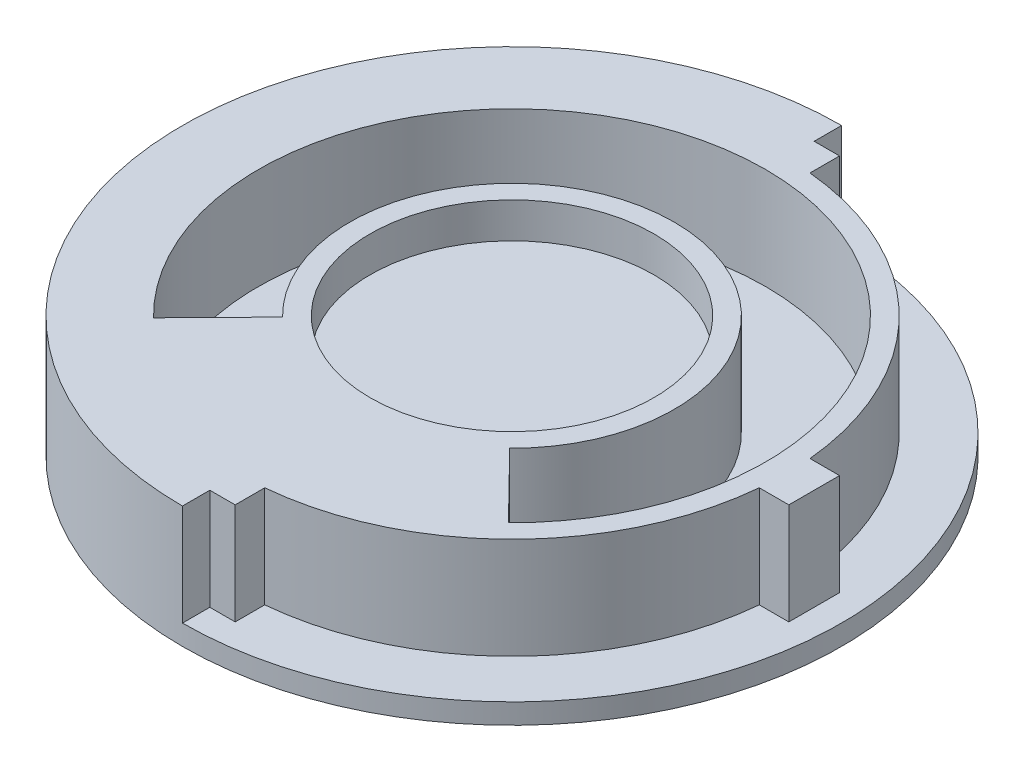
SolidWorks part; units mm, degrees
ref_plane "Front Plane" through (0, 0, 0) normal (0, 0, 1) x (1, 0, 0)
ref_plane "Top Plane" through (0, 0, 0) normal (0, 1, 0) x (1, 0, 0)
ref_plane "Right Plane" through (0, 0, 0) normal (1, 0, 0) x (0, 0, -1)
sketch "Sketch1" plane through (0, 0, 0) normal (0, 1, 0) x (1, 0, 0)
  line L0 (-17.5, -17.8536) -> (-11.2, -11.4263)
  line L1 (0, -55) -> (0, 55) construction
  line L2 (17.5, -17.8536) -> (11.2, -11.4263)
  line L4 (-17.5, -17.8536) -> (3.8221, -38.7535) construction
  circle A0 centre (0, 0) radius 27
  arc A1 (11.2, -11.4263) -> (-11.2, -11.4263) centre (0, 0) ccw
  arc A2 (17.5, -17.8536) -> (-17.5, -17.8536) centre (0, 0) ccw
  circle A3 centre (0, 0) radius 14
  arc A4 (16.5039, 11.7639) -> (14.35, -14.6399) centre (0.1913, -0.1952) cw construction
  circle A5 centre (0, 0) radius 19.9533 construction
  dimension "D1" = 54
  dimension "D2" = 2
  dimension "D3" = 9
  dimension "D4" = 2
  dimension "D5" = 35
extrude "Boss-Extrude1" add sketch "Sketch1" along normal blind 10
sketch "Sketch2" plane through (0, 0, 0) normal (0, -1, 0) x (1, 0, 0)
  circle A0 centre (0, 0) radius 32.5
  circle A1 centre (0, 0) radius 14 construction
  circle A2 centre (0, 0) radius 14 construction
  dimension "D1" = 65
extrude "Boss-Extrude2" add sketch "Sketch2" along normal blind 2
sketch "Sketch3" plane through (0, 0, 0) normal (0, 1, 0) x (1, 0, 0)
  line L0 (0, -5.5) -> (0, 5.5) construction
  line L1 (-2.5, 29.8) -> (2.5, 29.8)
  line L2 (-2.5, 29.8) -> (-2.5, 25.4032)
  line L3 (-2.5, 25.4032) -> (2.5, 25.4032)
  line L4 (2.5, 29.8) -> (2.5, 25.4032)
  line L5 (-2.5, 29.8) -> (2.5, 25.4032) construction
  line L6 (-2.5, 25.4032) -> (2.5, 29.8) construction
  line L7 (29.8, 2.5) -> (25.4032, 2.5)
  line L8 (29.8, 2.5) -> (29.8, -2.5)
  line L9 (29.8, -2.5) -> (25.4032, -2.5)
  line L10 (25.4032, 2.5) -> (25.4032, -2.5)
  line L11 (2.5, -29.8) -> (2.5, -25.4032)
  line L12 (2.5, -29.8) -> (-2.5, -29.8)
  line L13 (-2.5, -29.8) -> (-2.5, -25.4032)
  line L14 (2.5, -25.4032) -> (-2.5, -25.4032)
  line L15 (-29.8, -2.5) -> (-25.4032, -2.5)
  line L16 (-29.8, -2.5) -> (-29.8, 2.5)
  line L17 (-29.8, 2.5) -> (-25.4032, 2.5)
  line L18 (-25.4032, -2.5) -> (-25.4032, 2.5)
  circle A1 centre (0, 0) radius 27 construction
  point P0 (0, 27.6016)
  dimension "D2" = 29.8
  dimension "D1" = 5
  dimension "D3" = 4
extrude "Boss-Extrude3" add sketch "Sketch3" along normal blind 10
sketch "Sketch4" plane through (0, -2, 0) normal (0, -1, 0) x (1, 0, 0)
  circle A0 centre (0, 0) radius 7 construction
  circle A1 centre (0, -7) radius 0.9
  circle A2 centre (-7, 0) radius 0.9
  circle A3 centre (0, 7) radius 0.9
  circle A4 centre (7, 0) radius 0.9
  point P14 (0, 0)
  dimension "D1" = 14
  dimension "D2" = 1.8
  dimension "D3" = 4
extrude "Cut-Extrude1" cut sketch "Sketch4" against normal up to next
sketch "Sketch5" plane through (0, 0, 0) normal (0, 1, 0) x (1, 0, 0)
  line L0 (0, 29.8) -> (0, 32.5)
  line L1 (2.5, 29.8) -> (-2.5, 29.8) construction
  line L2 (0, -6.6) -> (0, 6.6) construction
  line L3 (0, -29.8) -> (0, -32.5)
  line L4 (0, 29.8) -> (-2.5, 29.8)
  line L5 (-2.5, 29.8) -> (-2.5, 26.884)
  line L6 (-26.884, 2.5) -> (-29.8, 2.5)
  line L7 (-29.8, 2.5) -> (-29.8, -2.5)
  line L8 (-29.8, -2.5) -> (-26.884, -2.5)
  line L9 (-2.5, -26.884) -> (-2.5, -29.8)
  line L10 (-2.5, -29.8) -> (0, -29.8)
  line L11 (-2.5, -29.8) -> (2.5, -29.8) construction
  circle A0 centre (0, 0) radius 32.5 construction
  arc A1 (0, 32.5) -> (0, -32.5) centre (0, 0) ccw
  arc A2 (-26.884, 2.5) -> (-2.5, 26.884) centre (0, 0) cw
  arc A3 (-26.884, -2.5) -> (-2.5, -26.884) centre (0, 0) ccw
extrude "Boss-Extrude4" add sketch "Sketch5" along normal up to surface (10 mm away) up to face at (0, 10, 0)
ref_plane "Plane1" through (0, 6.5, 0) normal (0, 1, 0) x (1, 0, 0)
sketch "Sketch6" plane through (0, 6.5, 0) normal (0, 1, 0) x (1, 0, 0)
  circle A0 centre (0, 0) radius 14
extrude "Boss-Extrude5" add sketch "Sketch6" against normal blind 2
